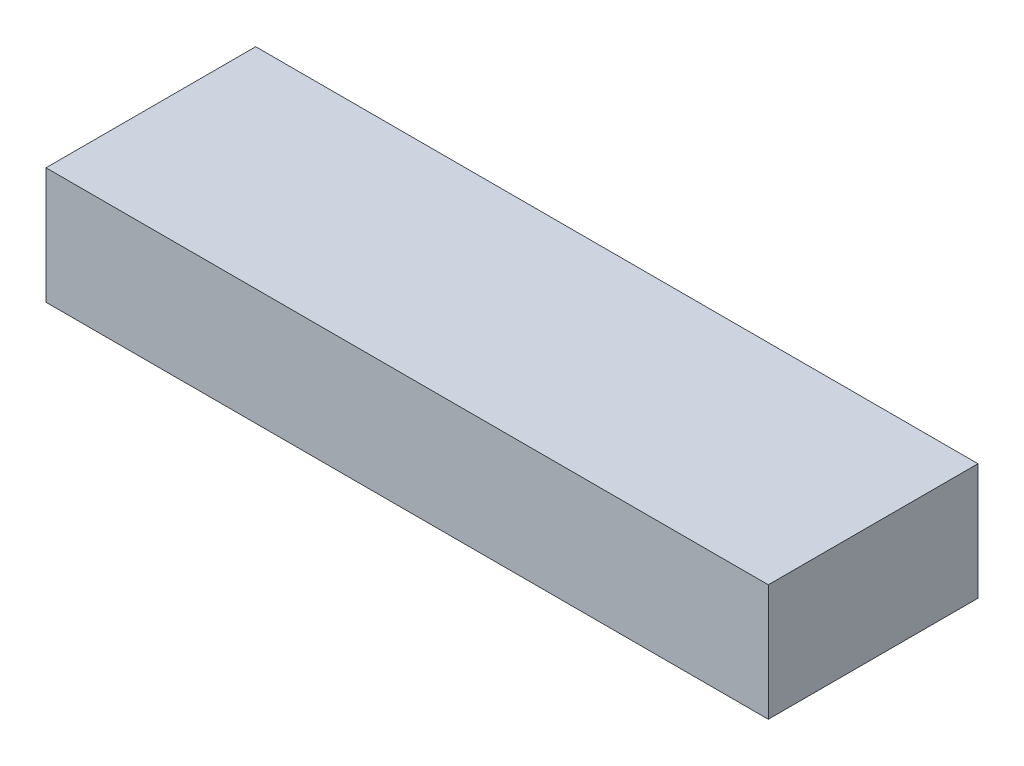
SolidWorks part; units mm, degrees
ref_plane "前视基准面" through (0, 0, 0) normal (0, 0, 1) x (1, 0, 0)
ref_plane "上视基准面" through (0, 0, 0) normal (0, 1, 0) x (1, 0, 0)
ref_plane "右视基准面" through (0, 0, 0) normal (1, 0, 0) x (0, 0, -1)
other "Configuration Table"
sketch "草图1" plane through (0, 0, 0) normal (0, 1, 0) x (1, 0, 0)
  line L1 (-77.5, -22.5) -> (77.5, -22.5)
  line L2 (-77.5, -22.5) -> (-77.5, 22.5)
  line L3 (-77.5, 22.5) -> (77.5, 22.5)
  line L4 (77.5, -22.5) -> (77.5, 22.5)
  line L5 (-77.5, -22.5) -> (77.5, 22.5) construction
  line L6 (-77.5, 22.5) -> (77.5, -22.5) construction
  point P0 (0, 0)
  dimension "D1" = 155
  dimension "D2" = 45
extrude "凸台-拉伸1" add sketch "草图1" along normal blind 25
